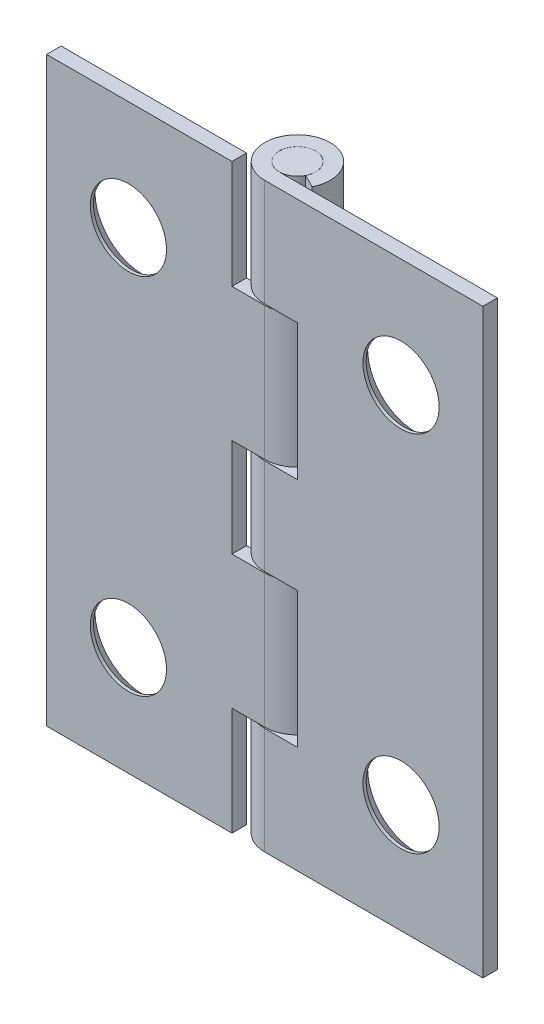
SolidWorks part; units mm, degrees
ref_plane "Front" through (0, 0, 0) normal (0, 0, 1) x (1, 0, 0)
ref_plane "Top" through (0, 0, 0) normal (0, 1, 0) x (1, 0, 0)
ref_plane "Right" through (0, 0, 0) normal (1, 0, 0) x (0, 0, -1)
sketch "Sketch1" plane through (0, 0, 0) normal (0, 1, 0) x (1, 0, 0)
  line L0 (0, -0.7937) -> (9.525, -0.7937)
  line L1 (9.525, -0.7937) -> (9.525, -1.4287)
  line L2 (9.525, -1.4287) -> (0, -1.4288)
  line L3 (1.2799, -0.635) -> (0.711, -0.3528)
  line L4 (0.711, -0.3528) -> (0, 0) construction
  line L5 (1.2799, -0.635) -> (1.2011, -0.7937) construction
  arc A0 (0.711, -0.3528) -> (0, -0.7937) centre (0, 0) ccw
  arc A1 (1.2799, -0.635) -> (0, -1.4288) centre (0, 0) ccw
  dimension "D1" = 0.1588
  dimension "K Pin Dia" = 1.5875
  dimension "B Half Width" = 9.525
  dimension "M Mat'l Thickness" = 0.635
extrude "Extrude1" add sketch "Sketch1" along normal mid plane 25.4
ref_plane "Plane2" through (5.9531, 0, 0) normal (1, 0, 0) x (0, 0, -1)
sketch "Sketch7" plane through (5.9531, 0, 0) normal (1, 0, 0) x (0, 0, -1)
  line L0 (1.8223, 7.9375) -> (-3.6624, 7.9375) construction
  line L1 (-0.7937, 7.9375) -> (-0.7937, 10.033)
  line L2 (-0.7937, 10.033) -> (-1.2905, 9.6012)
  line L3 (-1.2905, 9.6012) -> (-1.4287, 9.6012)
  line L4 (-1.4287, 9.6012) -> (-1.4287, 7.9375)
  line L5 (-1.4287, 7.9375) -> (-0.7937, 7.9375)
  line L6 (-0.7937, 5.842) -> (-1.2905, 6.2738) construction
  line L7 (-0.7937, 12.7) -> (-0.7937, -12.7) construction
  line L9 (-1.4287, 12.7) -> (-0.7937, 12.7) construction
  line L10 (-1.4287, 12.7) -> (-1.4287, -12.7) construction
  dimension "D1" = 82
  dimension "Screw Head Dia" = 4.191
  dimension "X Thru Dia" = 3.3274
  dimension "G" = 4.7625
revolve "Cut-Revolve1" cut sketch "Sketch7" angle 360 about L0
pattern_linear "LPattern2" count 2 spacing 15.875 along (0, -1, 0) of "Cut-Revolve1"
mirror "Mirror2" about plane through (0, 0, 0) normal (1, 0, 0) of bodies 114 108
sketch "Sketch4" plane through (0, 0, 0) normal (0, 0, 1) x (1, 0, 0)
  line L0 (-1.4288, 12.7) -> (-1.4288, 8.0264) construction
  line L1 (-1.4288, 8.0264) -> (1.4288, 8.0264)
  line L2 (1.4288, 8.0264) -> (1.4288, 2.0955)
  line L3 (1.4288, 2.0955) -> (-1.4288, 2.0955)
  line L4 (-1.4288, 2.0955) -> (-1.4288, -2.0955) construction
  line L5 (-1.4288, -2.0955) -> (1.4288, -2.0955)
  line L6 (1.4288, -2.0955) -> (1.4288, -8.0264)
  line L7 (1.4288, -8.0264) -> (-1.4288, -8.0264)
  line L8 (-1.4288, -8.0264) -> (-1.4288, -12.7) construction
  line L9 (9.525, -12.7) -> (0, -12.7) construction
  line L10 (9.525, 12.7) -> (0, 12.7) construction
  line L11 (-1.4288, 12.7) -> (-1.4288, -12.7) construction
  line L12 (1.4288, -12.7) -> (1.4288, 12.7) construction
  line L13 (-1.4288, -8.0264) -> (-1.4288, -2.0955)
  line L14 (-1.4288, 2.0955) -> (-1.4288, 8.0264)
  dimension "D" = 4.191
  dimension "C" = 16.0528
extrude "Cut-Extrude1" cut sketch "Sketch4" against normal through all and the other way through all
sketch "Sketch5" plane through (0, 0, 0) normal (0, 0, 1) x (1, 0, 0)
  line L0 (1.4288, -2.0955) -> (1.4288, -8.0264) construction
  line L1 (-1.4288, -12.7) -> (1.4288, -12.7)
  line L2 (-1.4288, -12.7) -> (-1.4288, -7.9756)
  line L3 (-1.4288, -7.9756) -> (1.4288, -7.9756)
  line L4 (1.4288, -12.7) -> (1.4288, -7.9756)
  line L5 (-1.4288, -8.0264) -> (-1.4288, -2.0955) construction
  line L6 (-1.4288, -2.1463) -> (1.4288, -2.1463)
  line L7 (-1.4288, -2.1463) -> (-1.4288, 2.1463)
  line L8 (-1.4288, 2.1463) -> (1.4288, 2.1463)
  line L9 (1.4288, -2.1463) -> (1.4288, 2.1463)
  line L10 (1.4288, 8.0264) -> (1.4288, 2.0955) construction
  line L11 (-1.4288, 8.0264) -> (1.4288, 8.0264) construction
  line L12 (-1.4288, 12.7) -> (1.4288, 12.7)
  line L13 (-1.4288, 12.7) -> (-1.4288, 7.9756)
  line L14 (-1.4288, 7.9756) -> (1.4288, 7.9756)
  line L15 (1.4288, 12.7) -> (1.4288, 7.9756)
  line L16 (1.4288, 2.0955) -> (-1.4288, 2.0955) construction
  line L17 (-1.4288, -2.0955) -> (1.4288, -2.0955) construction
  line L18 (1.4288, -8.0264) -> (-1.4288, -8.0264) construction
  dimension "D1" = 0.0508
  dimension "D2" = 0.0508
  dimension "D3" = 0.0508
  dimension "D4" = 0.0508
extrude "Cut-Extrude2" cut sketch "Sketch5" against normal through all and the other way through all
sketch "Sketch6" plane through (0, 0, 0) normal (0, 1, 0) x (1, 0, 0)
  line L0 (0, 0) -> (0, 0.7912) construction
  line L1 (0, 0.7912) -> (0, 0.7937) construction
  circle A0 centre (0, 0) radius 0.7912
  arc A1 (0.711, -0.3528) -> (0, -0.7937) centre (0, 0) ccw construction
  dimension "D1" = 0.0025
extrude "Extrude2" add sketch "Sketch6" against normal up to surface and the other way up to surface
equation "\"D1@Sketch1\"=\"M Mat'l Thickness@Sketch1\"/4"
